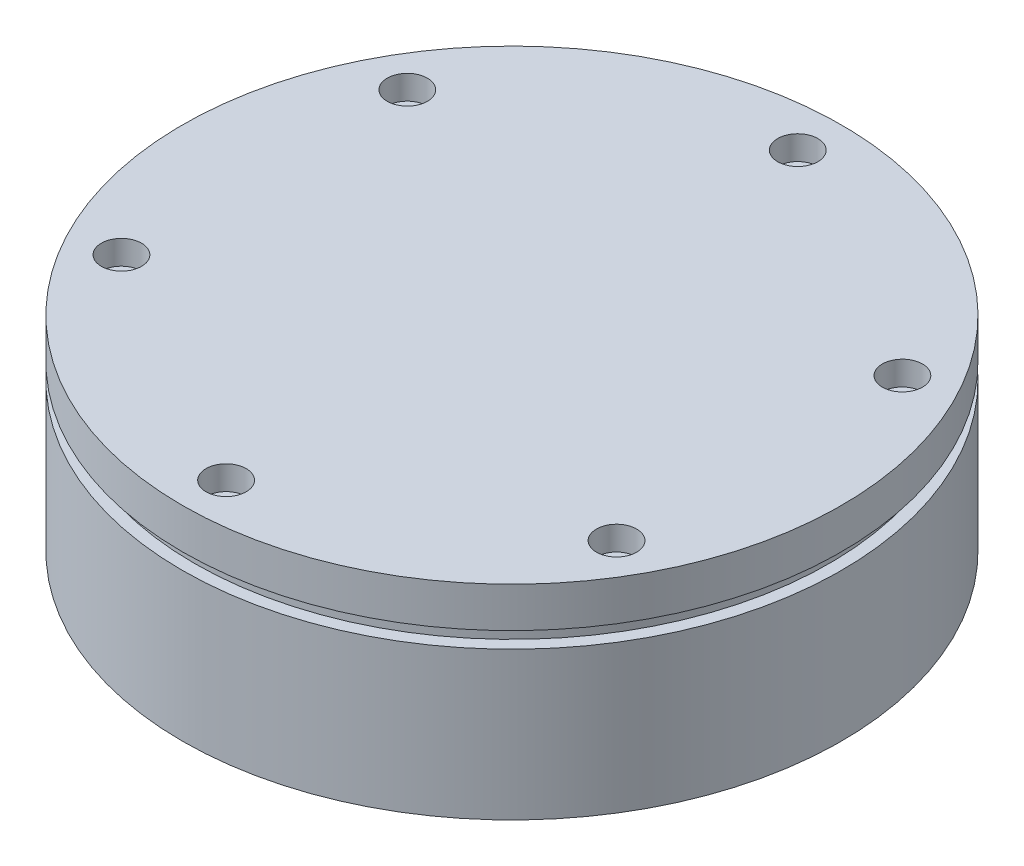
SolidWorks part; units mm, degrees
ref_plane "前视基准面" through (0, 0, 0) normal (0, 0, 1) x (1, 0, 0)
ref_plane "上视基准面" through (0, 0, 0) normal (0, 1, 0) x (1, 0, 0)
ref_plane "右视基准面" through (0, 0, 0) normal (1, 0, 0) x (0, 0, -1)
sketch "Sketch1" plane through (0, 0, 0) normal (0, 1, 0) x (1, 0, 0)
  circle A0 centre (0, 0) radius 41
  dimension "D1" = 82
extrude "Boss-Extrude1" add sketch "Sketch1" along normal blind 18.4
sketch "Sketch2" plane through (0, 18.4, 0) normal (0, 1, 0) x (1, 0, 0)
  circle A0 centre (0, 0) radius 39.5
  circle A1 centre (0, 0) radius 41 construction
  dimension "D1" = 1.5
extrude "Boss-Extrude2" add sketch "Sketch2" along normal blind 2
sketch "Sketch3" plane through (0, 20.4, 0) normal (0, 1, 0) x (1, 0, 0)
  circle A0 centre (0, 0) radius 41
  circle A1 centre (0, 0) radius 41 construction
extrude "Boss-Extrude3" add sketch "Sketch3" along normal blind 5
sketch "Sketch4" plane through (0, 0, 0) normal (0, -1, 0) x (1, 0, 0)
  line L0 (0, 0) -> (35.56, 0) construction
  line L1 (0, 0) -> (30.7959, 17.78) construction
  circle A0 centre (0, 0) radius 35.56 construction
  circle A1 centre (30.7959, 17.78) radius 2.5
  circle A5 centre (30.7959, -17.78) radius 2.5
  circle A6 centre (0, -35.56) radius 2.5
  circle A7 centre (-30.7959, -17.78) radius 2.5
  circle A8 centre (-30.7959, 17.78) radius 2.5
  circle A9 centre (0, 35.56) radius 2.5
  point P14 (0, 0)
  point P19 (0, 0)
  dimension "D1" = 71.12
  dimension "D2" = 5
  dimension "D3" = 30
  dimension "D4" = 6
extrude "Cut-Extrude1" cut sketch "Sketch4" against normal blind 5
sketch "Sketch5" plane through (0, 25.4, 0) normal (0, 1, 0) x (1, 0, 0)
  line L0 (35.56, 0) -> (0, 0) construction
  line L1 (0, 0) -> (30.7959, 17.78) construction
  circle A0 centre (0, 0) radius 35.56 construction
  circle A1 centre (30.7959, 17.78) radius 2.5
  circle A2 centre (30.7959, -17.78) radius 2.5
  circle A3 centre (0, -35.56) radius 2.5
  circle A4 centre (-30.7959, -17.78) radius 2.5
  circle A5 centre (-30.7959, 17.78) radius 2.5
  circle A6 centre (0, 35.56) radius 2.5
  point P19 (0, 0)
  dimension "D1" = 71.12
  dimension "D2" = 5
  dimension "D3" = 30
  dimension "D4" = 6
extrude "Cut-Extrude2" cut sketch "Sketch5" against normal blind 3
